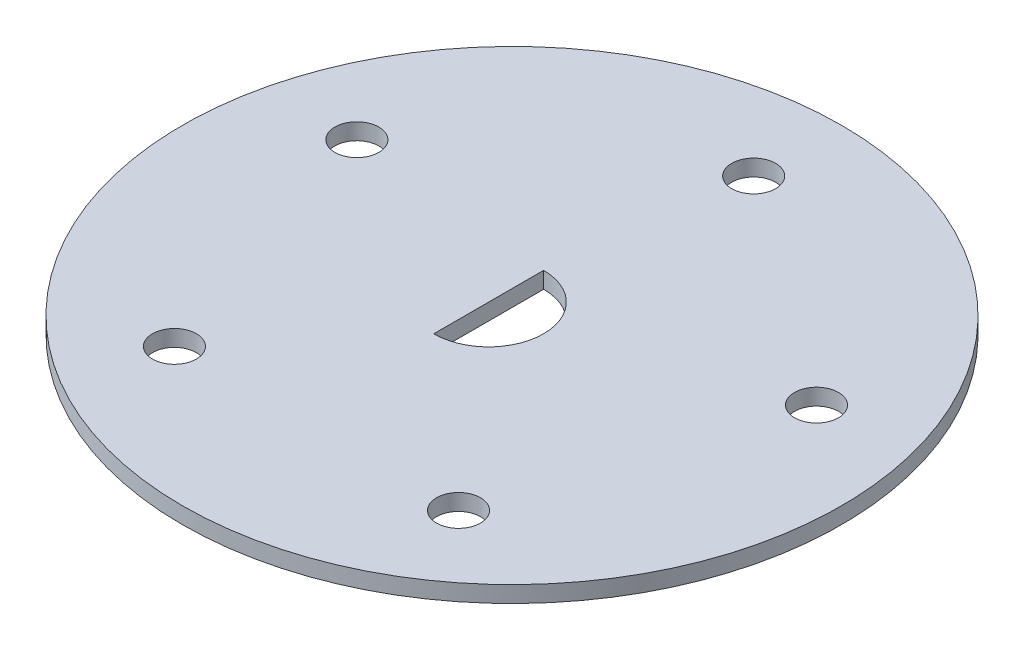
SolidWorks part; units mm, degrees
ref_plane "Front Plane" through (0, 0, 0) normal (0, 0, 1) x (1, 0, 0)
ref_plane "Top Plane" through (0, 0, 0) normal (0, 1, 0) x (1, 0, 0)
ref_plane "Right Plane" through (0, 0, 0) normal (1, 0, 0) x (0, 0, -1)
sketch "Sketch1" plane through (0, 0, 0) normal (0, 1, 0) x (1, 0, 0)
  line L1 (-2.695, 6.35) -> (-2.695, -6.35)
  circle A0 centre (0, 0) radius 38.1
  circle A2 centre (0, 27.94) radius 2.54
  arc A8 (-2.695, 6.35) -> (-2.695, -6.35) centre (-2.695, 0) cw
  circle A9 centre (26.5725, 8.6339) radius 2.54
  circle A10 centre (16.4227, -22.6039) radius 2.54
  circle A11 centre (-16.4227, -22.6039) radius 2.54
  circle A12 centre (-26.5725, 8.6339) radius 2.54
  point P18 (0, 0)
  point P19 (0, 0)
  dimension "D1" = 76.2
  dimension "D3" = 5.08
  dimension "D4" = 27.94
  dimension "D2" = 12.7
  dimension "D6" = 0
  dimension "D7" = 2.695
  dimension "D5" = 5
extrude "Boss-Extrude1" add sketch "Sketch1" along normal blind 1.8974
equation "\"D7@Sketch1\"=(4*0.25)/(3*3.14159265)"
